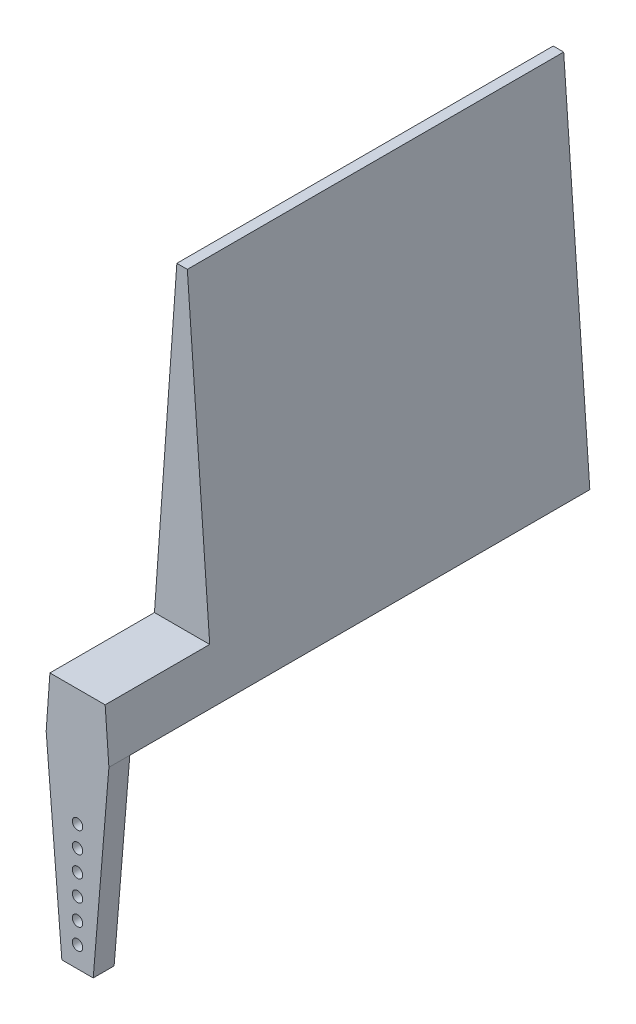
SolidWorks part; units mm, degrees
ref_plane "Front Plane" through (0, 0, 0) normal (0, 0, 1) x (1, 0, 0)
ref_plane "Top Plane" through (0, 0, 0) normal (0, 1, 0) x (1, 0, 0)
ref_plane "Right Plane" through (0, 0, 0) normal (1, 0, 0) x (0, 0, -1)
sketch "Sketch1" plane through (0, 0, 0) normal (0, 0, 1) x (1, 0, 0)
  line L0 (53, 55.7279) -> (74.1445, 55.7279) construction
  line L1 (63.0722, 55.7279) -> (64.0722, 55.7279)
  line L2 (64.0722, 55.7279) -> (66.5722, 20.7279)
  line L3 (63.5722, 20.7279) -> (63.5722, 55.7279) construction
  line L4 (63.0722, 55.7279) -> (60.5722, 20.7279)
  line L11 (54, 20.7279) -> (60.5722, 20.7279) construction
  line L16 (66.5722, 20.7279) -> (73.1445, 20.7279) construction
  line L17 (60.5722, 20.7279) -> (66.5722, 20.7279)
  point P1 (63.5722, 20.7279)
  point P19 (63.5722, 55.7279)
  point P20 (63.5722, 55.7279)
  dimension "D2" = 1
  dimension "D1" = 6
  dimension "D3" = 35
extrude "Boss-Extrude1" add sketch "Sketch1" against normal blind 36
sketch "Sketch3" plane through (0, 0, 0) normal (0, 0, 1) x (1, 0, 0)
  line L0 (60.5722, 20.7279) -> (60.9294, 25.7279)
  line L1 (63.0722, 55.7279) -> (60.5722, 20.7279) construction
  line L2 (60.9294, 25.7279) -> (66.2151, 25.7279)
  line L3 (66.5722, 20.7279) -> (64.0722, 55.7279) construction
  line L4 (66.2151, 25.7279) -> (66.5722, 20.7279)
  line L5 (66.5722, 20.7279) -> (60.5722, 20.7279)
  dimension "D1" = 5
extrude "Boss-Extrude3" add sketch "Sketch3" along normal blind 10
sketch "Sketch4" plane through (0, 0, 10) normal (0, 0, 1) x (1, 0, 0)
  line L1 (63.5722, 4.5279) -> (63.5722, 2.5279) construction
  line L5 (66.5722, 20.7279) -> (60.5722, 20.7279)
  line L7 (63.5722, 14.5279) -> (63.5722, 20.7279) construction
  line L12 (63.5722, 12.5279) -> (63.5722, 14.5279) construction
  line L13 (63.5722, 10.5279) -> (63.5722, 12.5279) construction
  line L14 (63.5722, 8.5279) -> (63.5722, 10.5279) construction
  line L15 (63.5722, 6.5279) -> (63.5722, 8.5279) construction
  line L16 (63.5722, 4.5279) -> (63.5722, 6.5279) construction
  line L17 (65.0722, 2.5279) -> (66.5722, 20.7279)
  line L18 (62.0722, 2.5279) -> (65.0722, 2.5279)
  line L19 (60.5722, 20.7279) -> (62.0722, 2.5279)
  circle A20 centre (63.5722, 14.5279) radius 0.5
  circle A24 centre (63.5722, 12.5279) radius 0.5
  circle A26 centre (63.5722, 10.5279) radius 0.5
  circle A28 centre (63.5722, 8.5279) radius 0.5
  circle A30 centre (63.5722, 4.5279) radius 0.5
  circle A32 centre (63.5722, 6.5279) radius 0.5
  point P13 (63.5722, 20.7279)
  dimension "D2" = 6.2
  dimension "D3" = 2
  dimension "D1" = 1
  dimension "D4" = 3
extrude "Boss-Extrude4" add sketch "Sketch4" against normal blind 2
equation "\"FlipperDepth\"=36"
equation "\"D1@Boss-Extrude1\"=\"FlipperDepth\""
equation "\"FlipperHandleLength\"=10"
equation "\"D1@Boss-Extrude3\"=\"FlipperHandleLength\""
equation "\"FlipperConnectionToServoHeight\"=18"
equation "\"FlipperHeight\"=35"
equation "\"D3@Sketch1\"=\"FlipperHeight\""
